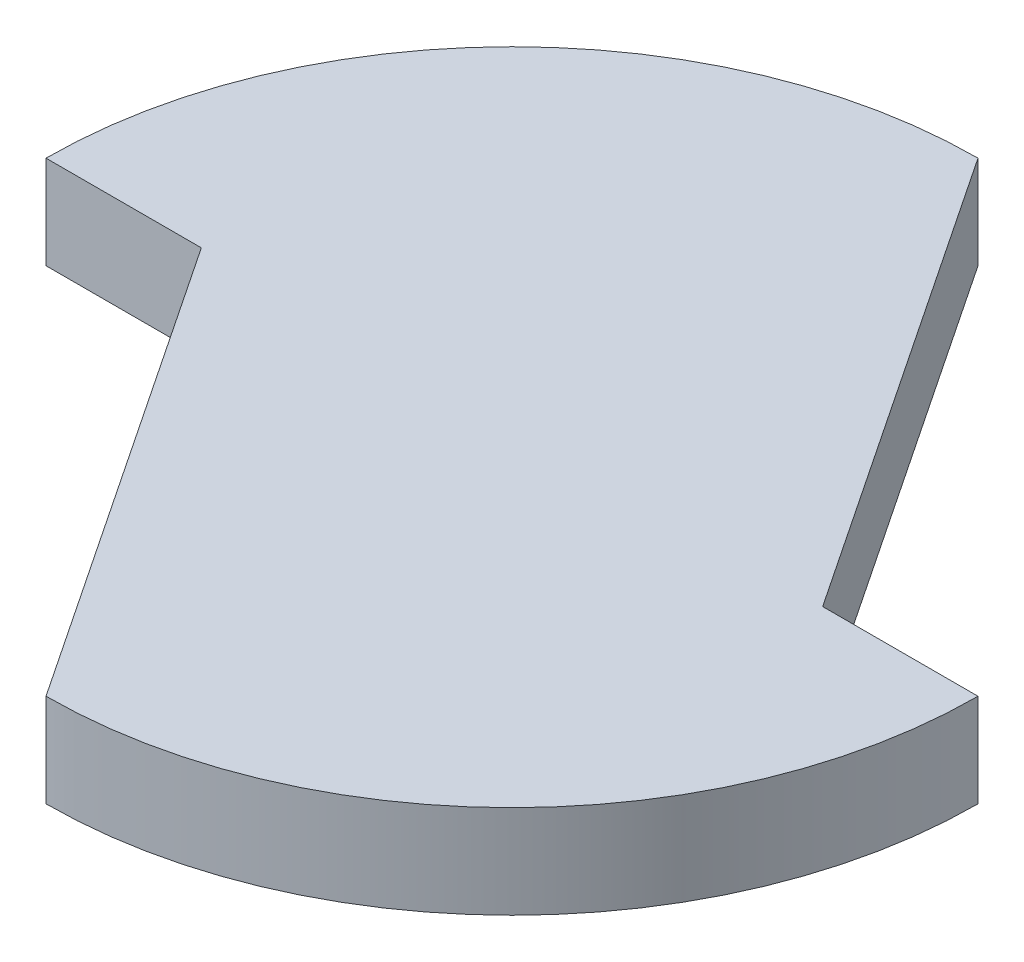
SolidWorks part; units mm, degrees
ref_plane "Front Plane" through (0, 0, 0) normal (0, 0, 1) x (1, 0, 0)
ref_plane "Top Plane" through (0, 0, 0) normal (0, 1, 0) x (1, 0, 0)
ref_plane "Right Plane" through (0, 0, 0) normal (1, 0, 0) x (0, 0, -1)
sketch "Sketch1" plane through (0, 0, 0) normal (0, 1, 0) x (1, 0, 0)
  circle A0 centre (0, 0) radius 15
extrude "Boss-Extrude1" add sketch "Sketch1" along normal blind 3
sketch "Sketch3" plane through (0, 3, 0) normal (0, 1, 0) x (1, 0, 0)
  line L0 (0, 0) -> (-15, 0)
  line L1 (-1.65, 0) -> (1.65, 0) construction
  line L2 (0, 0) -> (-10, 0)
  line L3 (0, -1.65) -> (0, 1.65) construction
  line L4 (0, 0) -> (-16.1289, 16.1289) construction
  line L5 (-10, 0) -> (0, -15)
  line L6 (0, 0) -> (15, 0)
  line L7 (0, 0) -> (10, 0)
  line L8 (10, 0) -> (0, 15)
  arc A0 (0, -15) -> (-15, 0) centre (0, 0) cw
  circle A1 centre (0, 0) radius 15 construction
  arc A2 (15, 0) -> (0, 15) centre (0, 0) ccw
  circle M4 centre (0, 0) radius 15
  dimension "D1" = 15
  dimension "D2" = 10
  dimension "D3" = 45
  dimension "D4" = 10
extrude "Cut-Extrude2" cut sketch "Sketch3" against normal blind 8 contours L5 L0 M4 | L8 L6 M4
